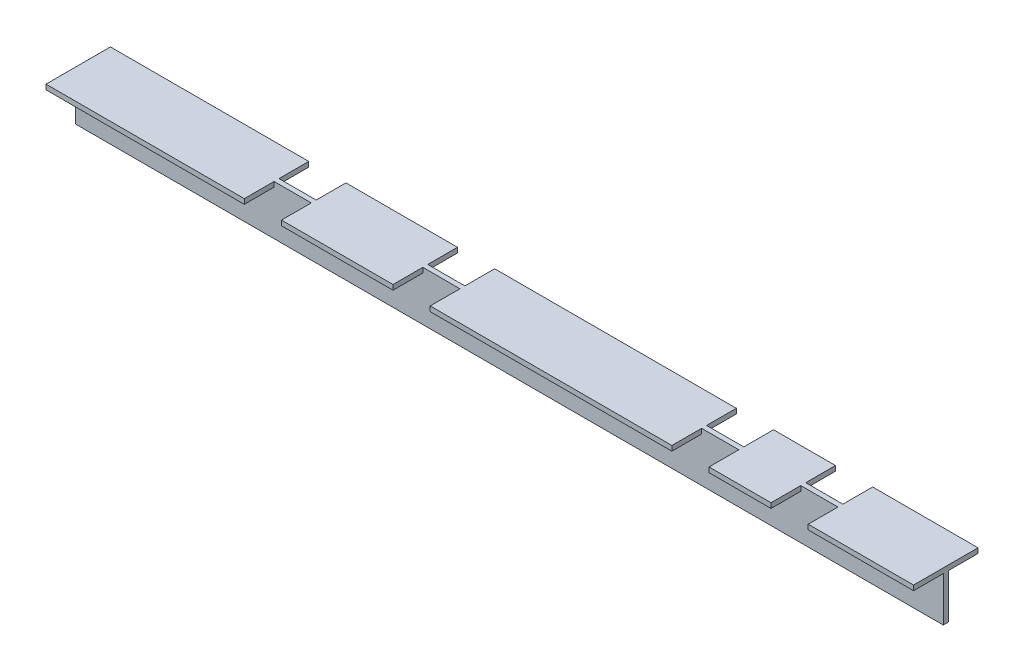
SolidWorks part; units mm, degrees
ref_plane "Front Plane" through (0, 0, 0) normal (0, 0, 1) x (1, 0, 0)
ref_plane "Top Plane" through (0, 0, 0) normal (0, 1, 0) x (1, 0, 0)
ref_plane "Right Plane" through (0, 0, 0) normal (1, 0, 0) x (0, 0, -1)
sketch "T" plane through (0, 0, 0) normal (1, 0, 0) x (0, 0, -1)
  line L0 (52, 0) -> (52, -80) construction
  line L1 (0, 0) -> (104, 0)
  line L2 (0, 0) -> (0, -8)
  line L3 (0, -8) -> (48, -8)
  line L4 (104, 0) -> (104, -8)
  line L6 (48, -8) -> (48, -80)
  line L7 (48, -80) -> (56, -80)
  line L8 (56, -8) -> (56, -80)
  line L9 (56, -8) -> (104, -8)
  dimension "D1" = 104
  dimension "D2" = 80
  dimension "D3" = 8
  dimension "D4" = 8
extrude "Boss-Extrude1" add sketch "T" along normal blind 1400
sketch "Sketch1" plane through (0, -8, 0) normal (0, -1, 0) x (-1, 0, 0)
  line L0 (-1400, 48) -> (0, 48) construction
  line L1 (-380, 48) -> (-320, 48)
  line L2 (-380, 48) -> (-380, 0)
  line L3 (-380, 0) -> (-320, 0)
  line L4 (-320, 48) -> (-320, 0)
  line L5 (-1400, 0) -> (0, 0) construction
  line L6 (-1400, 48) -> (0, 48) construction
  line L7 (-620, 48) -> (-560, 48)
  line L8 (-620, 48) -> (-620, 0)
  line L9 (-620, 0) -> (-560, 0)
  line L10 (-560, 48) -> (-560, 0)
  line L11 (-1230, 48) -> (-1170, 48)
  line L12 (-1230, 48) -> (-1230, 0)
  line L13 (-1230, 0) -> (-1170, 0)
  line L14 (-1170, 48) -> (-1170, 0)
  line L15 (-1400, 104) -> (0, 104) construction
  line L16 (-1230, 104) -> (-1170, 104)
  line L17 (-1230, 104) -> (-1230, 56)
  line L18 (-1230, 56) -> (-1170, 56)
  line L19 (-1170, 104) -> (-1170, 56)
  line L20 (-1400, 56) -> (0, 56) construction
  line L22 (-620, 104) -> (-560, 104)
  line L23 (-620, 104) -> (-620, 56)
  line L24 (-620, 56) -> (-560, 56)
  line L25 (-560, 104) -> (-560, 56)
  line L26 (-380, 104) -> (-320, 104)
  line L27 (-380, 104) -> (-380, 56)
  line L28 (-380, 56) -> (-320, 56)
  line L29 (-320, 104) -> (-320, 56)
  line L30 (-1400, 0) -> (0, 0) construction
  line L31 (-1070, 0) -> (-1010, 0)
  line L32 (-1070, 0) -> (-1070, 48)
  line L33 (-1070, 48) -> (-1010, 48)
  line L34 (-1010, 0) -> (-1010, 48)
  line L35 (-1400, 104) -> (0, 104) construction
  line L36 (-1070, 56) -> (-1010, 56)
  line L37 (-1070, 56) -> (-1070, 104)
  line L38 (-1070, 104) -> (-1010, 104)
  line L39 (-1010, 56) -> (-1010, 104)
  line L40 (-1400, 104) -> (-1400, 0) construction
  point P36 (-620, 80)
  point P37 (-1170, 80)
  dimension "D1" = 60
  dimension "D3" = 180
  dimension "D4" = 60
  dimension "D5" = 60
  dimension "D6" = 550
  dimension "D7" = 60
  dimension "D8" = 100
  dimension "D2" = 170
extrude "Cut-Extrude1" cut sketch "Sketch1" against normal through all contours L19 L18 L17 L16
equation "\"D4@Sketch1\"=\"D1@Sketch1\""
equation "\"D5@Sketch1\"=\"D1@Sketch1\""
equation "\"D7@Sketch1\"=\"D1@Sketch1\""
